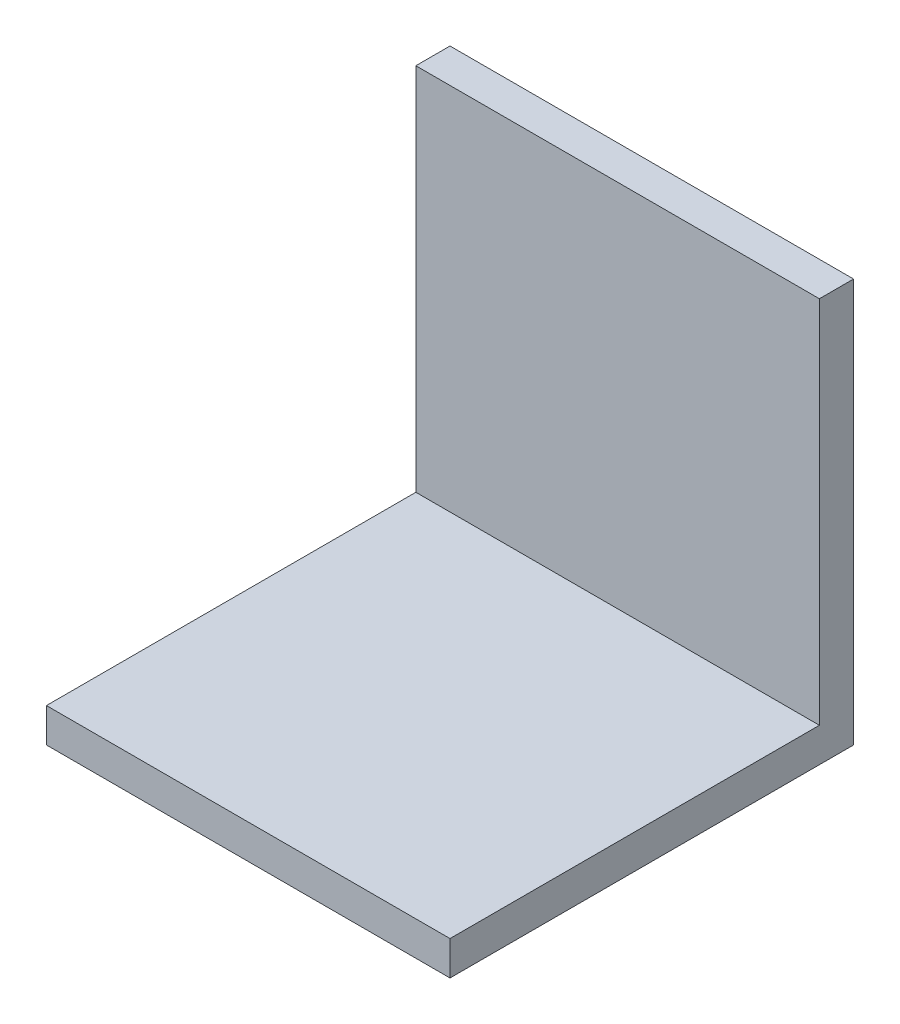
SolidWorks part; units mm, degrees
ref_plane "Front Plane" through (0, 0, 0) normal (0, 0, 1) x (1, 0, 0)
ref_plane "Top Plane" through (0, 0, 0) normal (0, 1, 0) x (1, 0, 0)
ref_plane "Right Plane" through (0, 0, 0) normal (1, 0, 0) x (0, 0, -1)
sketch "Sketch1" plane through (0, 0, 0) normal (0, 1, 0) x (1, 0, 0)
  line L1 (0, 0) -> (60, 0)
  line L2 (0, 0) -> (0, 60)
  line L3 (0, 60) -> (60, 60)
  line L4 (60, 0) -> (60, 60)
  dimension "D1" = 60
  dimension "D2" = 60
extrude "Boss-Extrude1" add sketch "Sketch1" along normal blind 5.08
sketch "Sketch2" plane through (0, 0, -60) normal (0, 0, -1) x (-1, 0, 0)
  line L1 (-60, 0) -> (0, 0)
  line L2 (-60, 0) -> (-60, 60)
  line L3 (-60, 60) -> (0, 60)
  line L4 (0, 0) -> (0, 60)
  dimension "D1" = 60
  dimension "D2" = 60
extrude "Boss-Extrude2" add sketch "Sketch2" against normal blind 5.08
